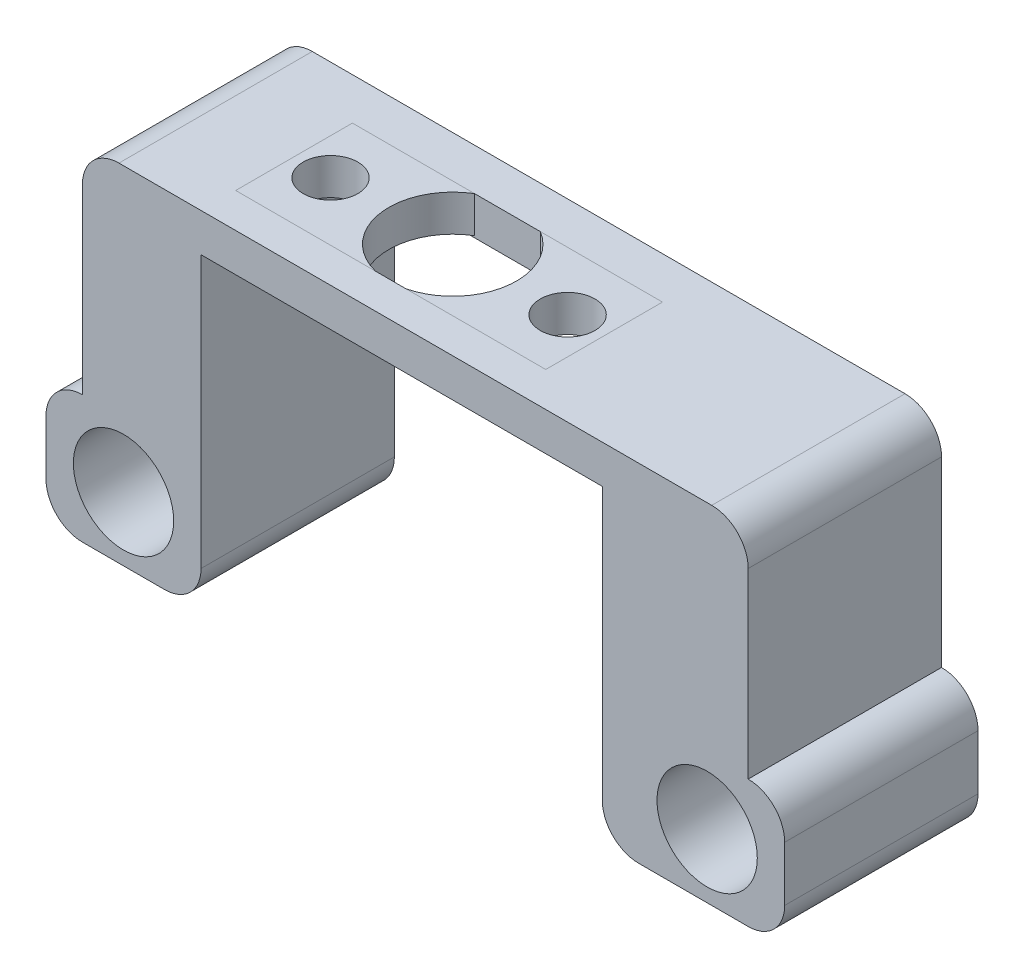
SolidWorks part; units mm, degrees
ref_plane "Alzado" through (0, 0, 0) normal (0, 0, 1) x (1, 0, 0)
ref_plane "Planta" through (0, 0, 0) normal (0, 1, 0) x (1, 0, 0)
ref_plane "Vista lateral" through (0, 0, 0) normal (1, 0, 0) x (0, 0, -1)
sketch "Croquis1" plane through (0, 0, 0) normal (0, 0, 1) x (1, 0, 0)
  line L1 (-46.433, -7.2866) -> (-5.933, -7.2866)
  line L2 (-46.433, -7.2866) -> (-46.433, -14.2866)
  line L3 (-46.433, -14.2866) -> (-5.933, -14.2866)
  line L4 (-5.933, -7.2866) -> (-5.933, -14.2866)
  circle A0 centre (-42.183, -10.7866) radius 2.75
  circle A1 centre (-10.183, -10.7866) radius 2.75
  dimension "D5" = 2
  dimension "D6" = 4.25
  dimension "D8" = 5.5
  dimension "D1" = 3.5
  dimension "D2" = 7
  dimension "D3" = 4.25
  dimension "D4" = 3.5
  dimension "D7" = 32
extrude "Saliente-Extruir1" add sketch "Croquis1" along normal blind 10.6
sketch "Croquis4" plane through (0, -14.2866, 0) normal (0, -1, 0) x (1, 0, 0)
  line L0 (-34.225, 5.3) -> (-34.8087, 5.3) construction
  line L1 (-24.641, 5.3) -> (-27.037, 9.45)
  line L2 (-27.037, 9.45) -> (-31.829, 9.45)
  line L3 (-31.829, 9.45) -> (-34.225, 5.3)
  line L4 (-34.225, 5.3) -> (-31.829, 1.15)
  line L5 (-31.829, 1.15) -> (-27.037, 1.15)
  line L6 (-27.037, 1.15) -> (-24.641, 5.3)
  line L7 (-46.433, 10.6) -> (-46.433, 0) construction
  line L8 (-46.433, 10.6) -> (-5.933, 10.6) construction
  circle A0 centre (-29.433, 5.3) radius 3.25
  circle A1 centre (-29.433, 5.3) radius 4.15 construction
  dimension "D1" = 17
  dimension "D2" = 8.3
  dimension "D3" = 1.15
sketch "Croquis5" plane through (0, -14.2866, 0) normal (0, -1, 0) x (1, 0, 0)
  circle A0 centre (-29.433, 5.3) radius 3.4
extrude "Cortar-Extruir4" cut sketch "Croquis5" against normal up to vertex (7 mm away)
fillet "Redondeo1" radius 2 4 edges at (-5.933, -7.2866, 5.3) (-5.933, -14.2866, 5.3) (-46.433, -14.2866, 5.3) (-46.433, -7.2866, 5.3)
sketch "Croquis7" plane through (0, -7.2866, 0) normal (0, 1, 0) x (1, 0, 0)
  line L0 (-29.433, -5.3) -> (-29.433, -8.7) construction
  line L1 (-29.433, -8.7) -> (-20.933, -8.7) construction
  line L2 (-20.933, -8.7) -> (-20.933, -2.3) construction
  line L3 (-20.933, -2.3) -> (-37.933, -2.3) construction
  line L4 (-37.933, -2.3) -> (-37.933, -8.7) construction
  line L5 (-37.933, -8.7) -> (-29.433, -8.7) construction
  line L6 (-20.933, -8.7) -> (-20.933, -2.3)
  line L7 (-20.933, -2.3) -> (-37.933, -2.3)
  line L8 (-37.933, -2.3) -> (-37.933, -8.7)
  line L9 (-37.933, -8.7) -> (-20.933, -8.7)
  circle A0 centre (-29.433, -5.3) radius 3.4 construction
  dimension "D1" = 17
  dimension "D2" = 6.4
  dimension "D3" = 8.5
extrude "Cortar-Extruir5" cut sketch "Croquis7" against normal blind 5
sketch "Croquis8" plane through (0, -12.2866, 0) normal (0, 1, 0) x (1, 0, 0)
  line L0 (-20.933, -8.7) -> (-20.933, -2.3) construction
  line L1 (-37.933, -2.3) -> (-37.933, -8.7) construction
  line L2 (-20.933, -2.3) -> (-27.833, -2.3) construction
  line L4 (-31.033, -2.3) -> (-37.933, -2.3) construction
  circle A0 centre (-22.933, -5.5) radius 1.5
  circle A1 centre (-35.933, -5.5) radius 1.5
  dimension "D2" = 3
  dimension "D3" = 2
  dimension "D1" = 2
  dimension "D4" = 3.2
  dimension "D5" = 3.2
extrude "Cortar-Extruir6" cut sketch "Croquis8" against normal up to vertex (2 mm away)
sketch "Croquis11" plane through (0, -7.2866, 0) normal (0, 1, 0) x (1, 0, 0)
  line L1 (-44.433, 0) -> (-7.933, 0)
  line L2 (-44.433, 0) -> (-44.433, -10.6)
  line L3 (-44.433, -10.6) -> (-7.933, -10.6)
  line L4 (-7.933, 0) -> (-7.933, -10.6)
  line L5 (-37.933, -2.3) -> (-20.933, -2.3)
  line L6 (-37.933, -2.3) -> (-37.933, -8.7)
  line L7 (-37.933, -8.7) -> (-20.933, -8.7)
  line L8 (-20.933, -2.3) -> (-20.933, -8.7)
extrude "Saliente-Extruir3" add sketch "Croquis11" along normal blind 12
sketch "Croquis12" plane through (0, 4.7134, 0) normal (0, 1, 0) x (1, 0, 0)
  line L1 (-37.933, -2.3) -> (-20.933, -2.3)
  line L2 (-37.933, -2.3) -> (-37.933, -8.7)
  line L3 (-37.933, -8.7) -> (-20.933, -8.7)
  line L4 (-20.933, -2.3) -> (-20.933, -8.7)
  circle A0 centre (-35.933, -5.5) radius 1.5
  circle A1 centre (-22.933, -5.5) radius 1.5
  circle A2 centre (-29.433, -5.3) radius 3.5
  line M10 (-20.933, -8.7) -> (-37.933, -8.7)
  line M11 (-37.933, -8.7) -> (-37.933, -2.3)
  line M12 (-37.933, -2.3) -> (-20.933, -2.3)
  line M13 (-20.933, -2.3) -> (-20.933, -8.7)
extrude "Saliente-Extruir4" add sketch "Croquis12" against normal blind 2 separate body contours A2 A0 M12 M11 M10 | A2 A1 M10 M13 M12
sketch "Croquis13" plane through (0, 0, 0) normal (0, 0, -1) x (-1, 0, 0)
  line L0 (29.433, -14.2866) -> (29.433, 4.7134) construction
  line L1 (31.829, -14.2866) -> (27.037, -14.2866) construction
  line L2 (7.933, 4.7134) -> (44.433, 4.7134) construction
  line L3 (37.933, -14.2866) -> (15.933, -14.2866)
  line L4 (44.433, -14.2866) -> (7.933, -14.2866) construction
  line L5 (37.933, -14.2866) -> (37.933, 2.6134)
  line L6 (37.933, 2.6134) -> (20.933, 2.6134)
  line L7 (46.433, -9.2866) -> (46.433, -12.2866) construction
  line L9 (15.933, -14.2866) -> (15.933, 2.6134)
  line L10 (15.933, 2.6134) -> (20.933, 2.6134)
  dimension "D1" = 8.5
  dimension "D2" = 17
  dimension "D3" = 22
  dimension "D4" = 16.9
extrude "Cortar-Extruir7" cut sketch "Croquis13" against normal up to vertex
fillet "Redondeo2" radius 2 4 edges at (-44.433, 4.7134, 5.3) (-7.933, 4.7134, 5.3) (-37.933, -14.2866, 5.3) (-15.933, -14.2866, 5.3)
